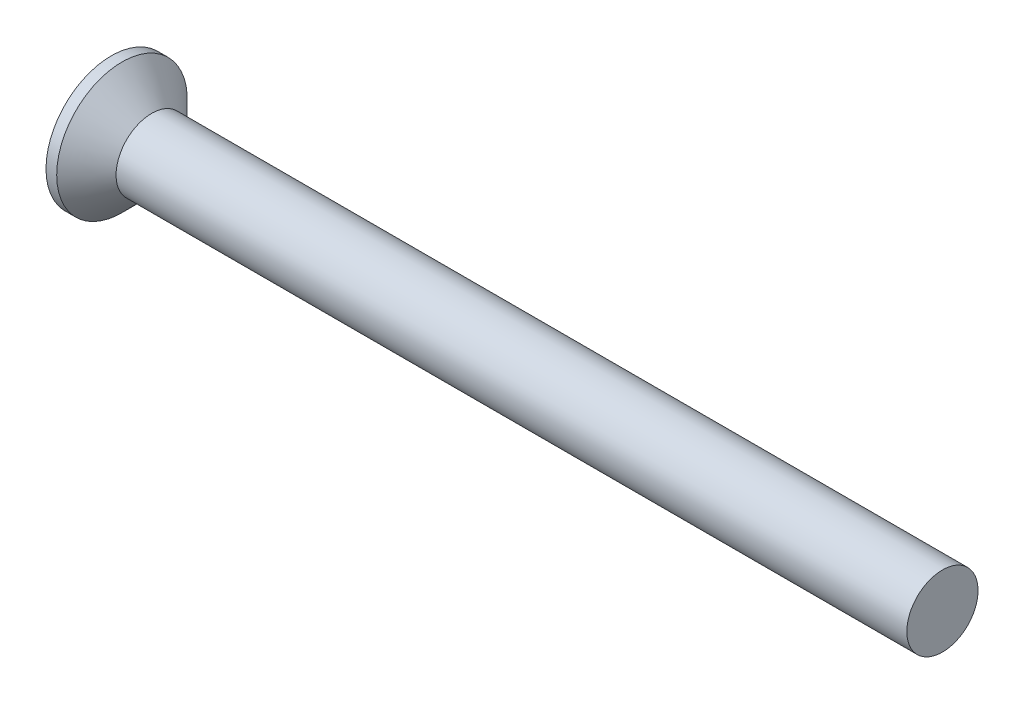
SolidWorks part; units mm, degrees
revolve "Base-Revolve" add sketch "BodySke" angle 360 about L5
sketch "BodySke" plane through (0, 0, 0) normal (0, 0, 1) x (1, 0, 0)
  line L0 (0, 0) -> (0, 2.75)
  line L1 (0, 2.75) -> (0.45, 2.75)
  line L2 (1.7, 1.5) -> (35, 1.5)
  line L3 (35, 1.5) -> (35, 0)
  line L4 (35, 0) -> (0, 0)
  line L5 (-6.35, 0) -> (82.55, 0) construction
  line L6 (1.7, -1.5) -> (35, -1.5) construction
  line L7 (0.45, -2.75) -> (1.7, -1.5) construction
  line L8 (0.45, 2.75) -> (1.7, 1.5)
  line L9 (0, -2.75) -> (0.45, -2.75) construction
  line L10 (2.2, 3.0875) -> (2.2, -6.4375) construction
  line L11 (0, 6.35) -> (0, -3.175) construction
  dimension "Diameter" = 3
  dimension "Length" = 35
  dimension "Head_ht" = 1.7
  dimension "Head_dia" = 5.5
  dimension "Head_ang" = 90
  dimension "D6" = 0.45
  dimension "Advance" = 0.5
  dimension "Thread_nom" = 35
cosmetic thread "ThreadCosmetic" [suppressed] parameters "Thread_length"=32.8, "Thread_minor"=2.439
extrude "Slot" [suppressed] cut sketch "Sketch2" against normal blind 0.9
sketch "Sketch2" plane through (0, 0, 0) normal (-1, 0, 0) x (0, 0, 1)
  line L0 (-2.75, -0.5) -> (2.75, -0.5)
  line L1 (-2.75, -0.5) -> (-2.75, 0.5)
  line L2 (2.75, 0.5) -> (-2.75, 0.5)
  line L3 (2.75, 0.5) -> (2.75, -0.5)
  dimension "Slot_width" = 1
  dimension "D1" = 0.5
  dimension "D2" = 5.5
  dimension "D3" = 2.75
ref_plane "Plane1" through (0, 0, 0) normal (0, 0, 1) x (1, 0, 0)
ref_plane "Plane2" through (0, 0, 0) normal (0, 1, 0) x (1, 0, 0)
ref_plane "Plane3" through (0, 0, 0) normal (1, 0, 0) x (0, 0, -1)
sketch "Sketch3" plane through (0, 0, 0) normal (-1, 0, 0) x (0, 0, 1)
  line L0 (-0.395, 1.55) -> (0.395, 1.55)
  line L1 (0.395, 1.55) -> (0.395, -1.55)
  line L2 (0.395, -1.55) -> (-0.395, -1.55)
  line L3 (-0.395, -1.55) -> (-0.395, 1.55)
  dimension "Cross_dia" = 3.1
  dimension "Cross_width" = 0.79
  dimension "D1" = 1.55
  dimension "D2" = 0.395
ref_plane "Plane4" through (2.08, 0, 0) normal (-1, 0, 0) x (0, 0, 1)
sketch "Sketch4" plane through (2.08, 0, 0) normal (-1, 0, 0) x (0, 0, 1)
  line L0 (-0.1975, 0.1975) -> (0.1975, 0.1975)
  line L3 (0.1975, 0.1975) -> (0.1975, -0.1975)
  line L4 (0.1975, -0.1975) -> (-0.1975, -0.1975)
  line L5 (-0.1975, -0.1975) -> (-0.1975, 0.1975)
  dimension "D2" = 0.395
  dimension "D1" = 0.395
  dimension "D3" = 0.1975
  dimension "D4" = 0.1975
loft "Cross" cut profiles "Sketch3", "Sketch4"
pattern_circular "CirPattern1" count 2 every 90 about axis through (0, 0, 0) along (1, 0, 0) of "Cross"
sketch "ThdSchSke" plane through (0, 0, 0) normal (0, 0, 1) x (1, 0, 0)
  line L0 (2.2, -1.2195) -> (2.0036, -1.5)
  line L1 (2.2, -1.2195) -> (2.3964, -1.5)
  line L2 (2.3964, -1.5) -> (2.3964, -1.875)
  line L3 (-3.175, 0) -> (5.1513, 0) construction
  line L5 (2.3964, -1.875) -> (2.0036, -1.875)
  line L6 (2.0036, -1.875) -> (2.0036, -1.5)
  line L7 (0, 2.75) -> (0, -2.75) construction
  dimension "Diameter" = 3
  dimension "Thread_minor" = 2.439
  dimension "Start" = 2.2
revolve "ThreadSchematic" [suppressed] cut sketch "ThdSchSke" angle 360 about L3
pattern_linear "ThdSchPat" [suppressed]
equation "\"D1@Sketch3\" = \"Cross_dia@Sketch3\" / 2"
equation "\"D2@Sketch3\" = \"Cross_width@Sketch3\" / 2"
equation "\"D1@Sketch4\" = \"Cross_width@Sketch3\" *.5"
equation "\"D2@Sketch4\" = \"D1@Sketch4\""
equation "\"D4@Sketch4\" = \"D2@Sketch4\" / 2"
equation "\"D3@Sketch4\" = \"D1@Sketch4\" / 2"
equation "\"D1@Sketch2\" = \"Slot_width@Sketch2\" / 2"
equation "\"D2@Sketch2\" = \"Head_dia@BodySke\""
equation "\"D3@Sketch2\" = \"D2@Sketch2\" / 2"
equation "\"Thread_length@ThreadCosmetic\" = ((sgn( (\"Length@BodySke\" - \"Advance@BodySke\" - \"Head_ht@BodySke\" ) - \"Thread_nom@BodySke\" )-1)*( (\"Length@BodySke\" - \"Advance@BodySke\" - \"Head_ht@BodySke\" ) - \"Thread_nom@BodySke\" ))/-2+ \"Thread_nom@BodySke\""
equation "\"Thread_minor@ThdSchSke\" = \"Thread_minor@ThreadCosmetic\""
equation "\"Diameter@ThdSchSke\" = \"Diameter@BodySke\""
equation "\"Overcut@ThdSchSke\" = \"Diameter@BodySke\" * 1.25"
equation "\"Start@ThdSchSke\" = 0.000001 + \"Length@BodySke\" - \"Thread_length@ThreadCosmetic\"  '---Countersunk---"
equation "\"Num_threads@ThdSchPat\" = int( \"Thread_length@ThreadCosmetic\" / \"Advance@BodySke\" + 0.999 )  + 1"
equation "\"Advance@ThdSchPat\" = \"Thread_length@ThreadCosmetic\" /  (\"Num_threads@ThdSchPat\" - 1) 'relax it"
